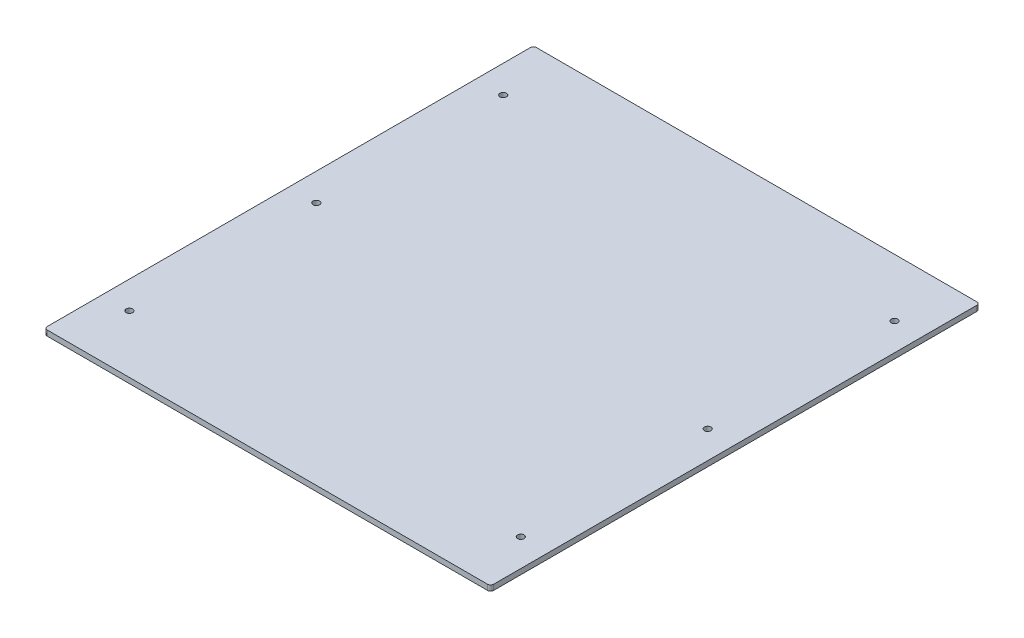
SolidWorks part; units mm, degrees
material "ABS PC"
ref_plane "Front Plane" through (0, 0, 0) normal (0, 0, 1) x (1, 0, 0)
ref_plane "Top Plane" through (0, 0, 0) normal (0, 1, 0) x (1, 0, 0)
ref_plane "Right Plane" through (0, 0, 0) normal (1, 0, 0) x (0, 0, -1)
sketch "Sketch1" plane through (0, 0, 0) normal (0, 1, 0) x (1, 0, 0)
  line L0 (231.775, 508) -> (231.775, 0) construction
  line L1 (0, 0) -> (463.55, 0)
  line L2 (0, 0) -> (0, 508)
  line L3 (0, 508) -> (463.55, 508)
  line L4 (463.55, 0) -> (463.55, 508)
  line L5 (28.575, 59.944) -> (28.575, 254) construction
  line L6 (28.575, 254) -> (28.575, 448.056) construction
  line L7 (434.975, 254) -> (434.975, 448.056) construction
  line L8 (434.975, 59.944) -> (434.975, 254) construction
  line L9 (28.575, 254) -> (231.775, 254) construction
  circle A0 centre (28.575, 59.944) radius 3.3782
  circle A1 centre (28.575, 254) radius 3.3782
  circle A2 centre (28.575, 448.056) radius 3.3782
  circle A3 centre (434.975, 448.056) radius 3.3782
  circle A4 centre (434.975, 254) radius 3.3782
  circle A5 centre (434.975, 59.944) radius 3.3782
  dimension "D3" = 6.7564
  dimension "D1" = 463.55
  dimension "D2" = 194.056
  dimension "D5" = 28.575
  dimension "D6" = 508
extrude "Boss-Extrude1" add sketch "Sketch1" along normal blind 5.588
fillet "Fillet1" radius 3.175 4 edges at (0, 2.794, -508) (463.55, 2.794, -508) (0, 2.794, 0) (463.55, 2.794, 0)
